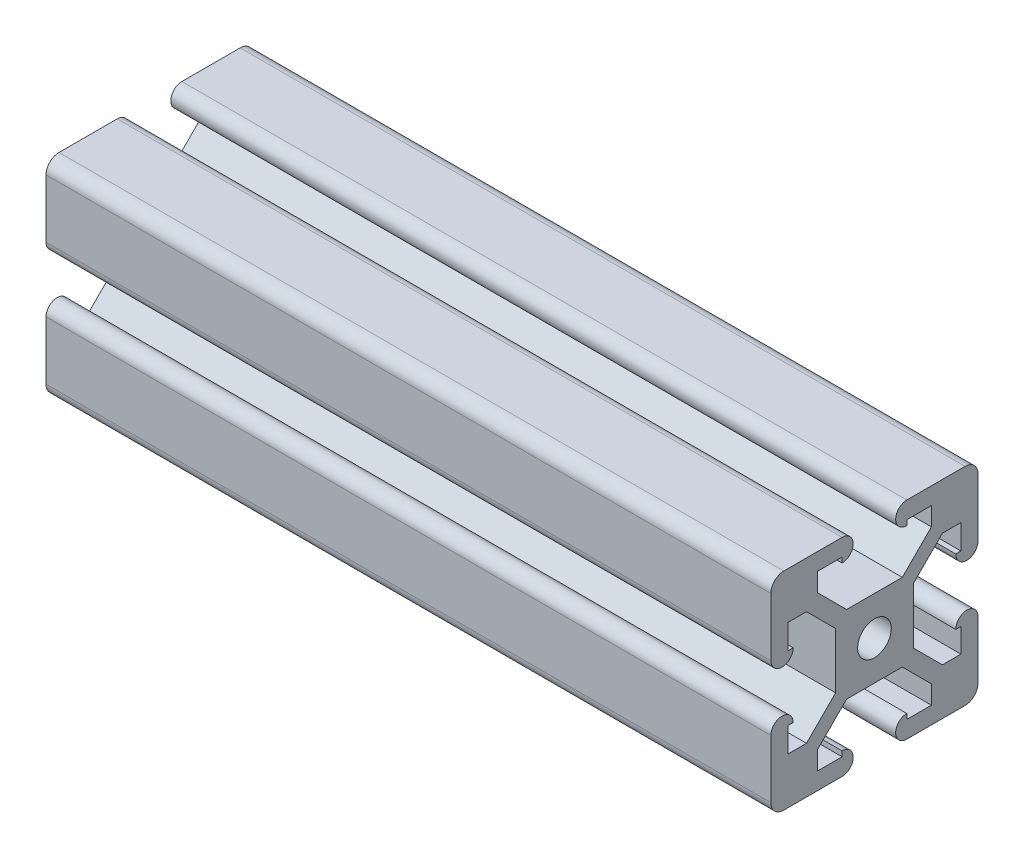
SolidWorks part; units mm, degrees
material "6063-O"
ref_plane "Front Plane" through (0, 0, 0) normal (0, 0, 1) x (1, 0, 0)
ref_plane "Top Plane" through (0, 0, 0) normal (0, 1, 0) x (1, 0, 0)
ref_plane "Right Plane" through (0, 0, 0) normal (1, 0, 0) x (0, 0, -1)
sketch "Sketch1" plane through (0, 0, 0) normal (1, 0, 0) x (0, 0, -1)
  line L0 (-20, 17.5) -> (-20, 6.25)
  line L1 (-17.5, 20) -> (-6.25, 20)
  line L2 (20, 17.5) -> (20, 6.25)
  line L3 (-17.5, -20) -> (-6.25, -20)
  line L4 (-6.25, 15.7) -> (-6.25, 16.7)
  line L5 (-6.25, 16.7) -> (-11.0055, 16.7)
  line L6 (6.25, 20) -> (17.5, 20)
  line L7 (-15.7, 6.25) -> (-16.7, 6.25)
  line L8 (-16.7, 6.25) -> (-16.7, 11.0055)
  line L9 (-16.7, 11.0055) -> (-13.1269, 11.0055)
  line L10 (-13.1269, 11.0055) -> (-7.5, 5.3787)
  line L11 (-7.5, 5.3787) -> (-7.5, -5.3787)
  line L12 (-7.5, -5.3787) -> (-13.1269, -11.0055)
  line L13 (-13.1269, -11.0055) -> (-16.7, -11.0055)
  line L14 (-16.7, -11.0055) -> (-16.7, -6.25)
  line L15 (-16.7, -6.25) -> (-15.7, -6.25)
  line L16 (-20, -6.25) -> (-20, -17.5)
  line L17 (6.25, -20) -> (17.5, -20)
  line L18 (-11.0055, 16.7) -> (-11.0055, 13.1269)
  line L19 (-11.0055, 13.1269) -> (-5.3787, 7.5)
  line L20 (-5.3787, 7.5) -> (5.3787, 7.5)
  line L21 (5.3787, 7.5) -> (11.0055, 13.1269)
  line L22 (11.0055, 13.1269) -> (11.0055, 16.7)
  line L23 (11.0055, 16.7) -> (6.25, 16.7)
  line L24 (6.25, 16.7) -> (6.25, 15.7)
  line L26 (20, -17.5) -> (20, -6.376)
  line L27 (-6.25, -15.7) -> (-6.25, -16.7)
  line L28 (-6.25, -16.7) -> (-11.0055, -16.7)
  line L29 (-11.0055, -16.7) -> (-11.0055, -13.1269)
  line L30 (-11.0055, -13.1269) -> (-5.3787, -7.5)
  line L31 (-5.3787, -7.5) -> (5.3787, -7.5)
  line L32 (5.3787, -7.5) -> (11.0055, -13.1269)
  line L33 (11.0055, -13.1269) -> (11.0055, -16.7)
  line L34 (11.0055, -16.7) -> (6.25, -16.7)
  line L35 (6.25, -16.7) -> (6.25, -15.7)
  line L36 (15.7, -6.376) -> (16.7, -6.376)
  line L37 (16.7, -6.376) -> (16.7, -11.0055)
  line L38 (16.7, -11.0055) -> (13.1269, -11.0055)
  line L39 (13.1269, -11.0055) -> (7.5, -5.3787)
  line L40 (7.5, -5.3787) -> (7.5, 5.3787)
  line L41 (7.5, 5.3787) -> (13.1269, 11.0055)
  line L42 (13.1269, 11.0055) -> (16.7, 11.0055)
  line L43 (16.7, 11.0055) -> (16.7, 6.25)
  line L44 (16.7, 6.25) -> (15.7, 6.25)
  circle A0 centre (0, 0) radius 3.25
  arc A1 (-15.7, -6.25) -> (-20, -6.25) centre (-17.85, -6.25) ccw
  arc A2 (-15.7, 6.25) -> (-20, 6.25) centre (-17.85, 6.25) cw
  arc A3 (-20, 17.5) -> (-17.5, 20) centre (-17.5, 17.5) cw
  arc A4 (-20, -17.5) -> (-17.5, -20) centre (-17.5, -17.5) ccw
  arc A5 (-6.25, 20) -> (-6.25, 15.7) centre (-6.25, 17.85) cw
  arc A6 (6.25, 20) -> (6.25, 15.7) centre (6.25, 17.85) ccw
  arc A7 (17.5, 20) -> (20, 17.5) centre (17.5, 17.5) cw
  arc A8 (17.5, -20) -> (20, -17.5) centre (17.5, -17.5) ccw
  arc A9 (20, 6.25) -> (15.7, 6.25) centre (17.85, 6.25) cw
  arc A10 (20, -6.376) -> (15.7, -6.376) centre (17.85, -6.376) ccw
  arc A11 (-6.25, -20) -> (-6.25, -15.7) centre (-6.25, -17.85) ccw
  arc A12 (6.25, -20) -> (6.25, -15.7) centre (6.25, -17.85) cw
  point P13 (-17.85, -4.1)
  point P15 (-17.85, 4.1)
  point P29 (0, 7.5)
  dimension "D1" = 6.5
  dimension "D4" = 2.5
  dimension "D10" = 15
  dimension "D2" = 40
  dimension "D3" = 1
  dimension "D5" = 3.3
  dimension "D6" = 8.2
  dimension "D7" = 40
  dimension "D8" = 15
  dimension "D9" = 20
  dimension "D11" = 20
  dimension "D12" = 3.3
  dimension "D13" = 7.5
  dimension "D14" = 7.5
  dimension "D15" = 3
extrude "Boss-Extrude1" add sketch "Sketch1" along normal blind 140
